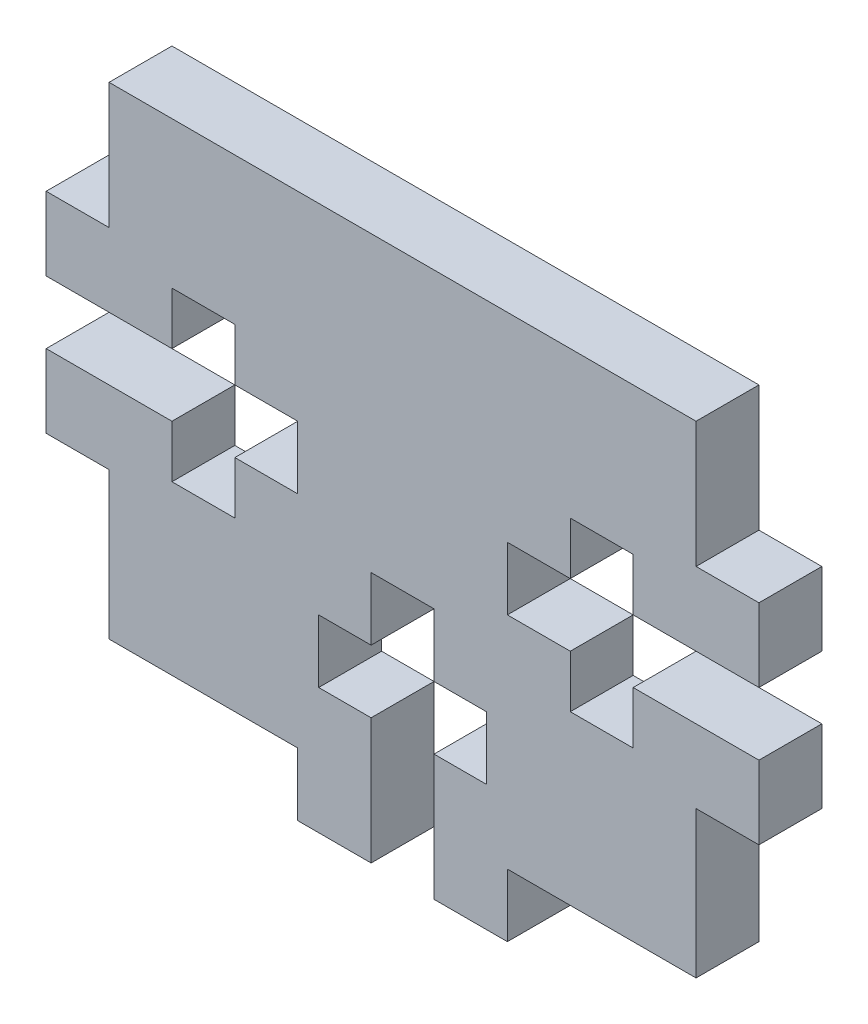
SolidWorks part; units mm, degrees
ref_plane "前视基准面" through (0, 0, 0) normal (0, 0, 1) x (1, 0, 0)
ref_plane "上视基准面" through (0, 0, 0) normal (0, 1, 0) x (1, 0, 0)
ref_plane "右视基准面" through (0, 0, 0) normal (1, 0, 0) x (0, 0, -1)
other "Configuration Table"
sketch "草图1" plane through (0, 0, 0) normal (0, 0, 1) x (1, 0, 0)
  line L0 (0, 11.0299) -> (0, -10.8894) construction
  line L1 (-14, 12) -> (14, 12)
  line L2 (-14, 12) -> (-14, -12)
  line L3 (-14, -12) -> (14, -12)
  line L4 (14, 12) -> (14, -12)
  line L5 (-14, 12) -> (14, -12) construction
  line L6 (-14, -12) -> (14, 12) construction
  line L7 (-14, -5) -> (-17, -5)
  line L8 (-14, -5) -> (-14, 5)
  line L9 (-14, 5) -> (-17, 5)
  line L10 (-17, -5) -> (-17, 5)
  line L11 (14, 5) -> (17, 5)
  line L12 (17, -5) -> (17, 5)
  line L13 (14, -5) -> (17, -5)
  line L14 (14, -5) -> (14, 5)
  line L16 (-5, -12) -> (5, -12)
  line L17 (-5, -12) -> (-5, -15)
  line L18 (-5, -15) -> (5, -15)
  line L19 (5, -12) -> (5, -15)
  point P0 (0, 0)
  point P10 (-17, 0)
  point P21 (0, -15)
  dimension "D1" = 28
  dimension "D2" = 24
  dimension "D3" = 3
  dimension "D4" = 10
extrude "凸台-拉伸1" add sketch "草图1" along normal blind 3 contours L4 L1 L2 L3 | L10 L7 L2 L9 | L4 L13 L12 L11 | L19 L3 L17 L18
sketch "草图2" plane through (0, 0, 3) normal (0, 0, 1) x (1, 0, 0)
  line L0 (-17, -5) -> (-17, 5) construction
  line L1 (-29, 1.5) -> (-5, 1.5)
  line L2 (-29, 1.5) -> (-29, -1.5)
  line L3 (-29, -1.5) -> (-5, -1.5)
  line L4 (-5, 1.5) -> (-5, -1.5)
  line L5 (-29, 1.5) -> (-5, -1.5) construction
  line L6 (-29, -1.5) -> (-5, 1.5) construction
  line L7 (-17, 0) -> (-9.5, 0) construction
  line L8 (0, 6.8052) -> (0, -6.843) construction
  line L9 (-11, 4) -> (-8, 4)
  line L10 (-11, 4) -> (-11, -4)
  line L11 (-11, -4) -> (-8, -4)
  line L12 (-8, 4) -> (-8, -4)
  line L13 (-11, 4) -> (-8, -4) construction
  line L14 (-11, -4) -> (-8, 4) construction
  line L15 (11, -4) -> (8, 4) construction
  line L16 (11, 4) -> (8, -4) construction
  line L17 (17, 0) -> (9.5, 0) construction
  line L18 (29, -1.5) -> (5, 1.5) construction
  line L19 (29, 1.5) -> (5, -1.5) construction
  line L20 (8, 4) -> (8, -4)
  line L21 (11, -4) -> (8, -4)
  line L22 (11, 4) -> (11, -4)
  line L23 (11, 4) -> (8, 4)
  line L24 (5, 1.5) -> (5, -1.5)
  line L25 (29, -1.5) -> (5, -1.5)
  line L26 (29, 1.5) -> (29, -1.5)
  line L27 (29, 1.5) -> (5, 1.5)
  line L28 (-14, -12) -> (14, 12) construction
  line L29 (-5, -15) -> (5, -15) construction
  line L30 (-1.5, -3) -> (1.5, -3)
  line L31 (-1.5, -3) -> (-1.5, -27)
  line L32 (-1.5, -27) -> (1.5, -27)
  line L33 (1.5, -3) -> (1.5, -27)
  line L34 (-1.5, -3) -> (1.5, -27) construction
  line L35 (-1.5, -27) -> (1.5, -3) construction
  line L36 (0, -15) -> (0, -7.5) construction
  line L38 (-4, -6) -> (4, -6)
  line L39 (-4, -6) -> (-4, -9)
  line L40 (-4, -9) -> (4, -9)
  line L41 (4, -6) -> (4, -9)
  line L42 (-4, -6) -> (4, -9) construction
  line L43 (-4, -9) -> (4, -6) construction
  point P0 (-17, 0)
  point P26 (17, 0)
  point P31 (0, -15)
  line M7 (-17, 5) -> (-17, -5)
  line M13 (17, -5) -> (17, 5)
  line M42 (-5, -15) -> (5, -15)
  dimension "D1" = 3
  dimension "D2" = 24
  dimension "D3" = 3
  dimension "D4" = 8
  dimension "D5" = 6
  dimension "D6" = 24
  dimension "D7" = 3
  dimension "D8" = 3
  dimension "D9" = 8
  dimension "D10" = 6
extrude "切除-拉伸1" cut sketch "草图2" against normal blind 3 contours L10 L1 L3 M7 | L12 L9 L10 L1 | L12 L1 L10 L3 | L12 L3 L10 L11 | L1 L12 L3 L4 | L20 L27 L24 L25 | L27 L22 L23 L20 | L22 L27 L20 L25 | L22 L25 L20 L21 | L27 L22 L25 M13 | L39 L40 L31 L38 | L31 L38 L33 L30 | L31 L40 L33 L38 | L41 L38 L33 L40 | L40 L31 L33 M42
sketch "草图3" plane through (0, 0, 3) normal (0, 0, 1) x (1, 0, 0)
  line L0 (14, 12) -> (14, 5) construction
  line L1 (-14, 12) -> (14, 12)
  line L2 (-14, 12) -> (-14, 11)
  line L3 (-14, 11) -> (14, 11)
  line L4 (14, 12) -> (14, 11)
  dimension "D1" = 1
extrude "切除-拉伸2" cut sketch "草图3" against normal blind 3
